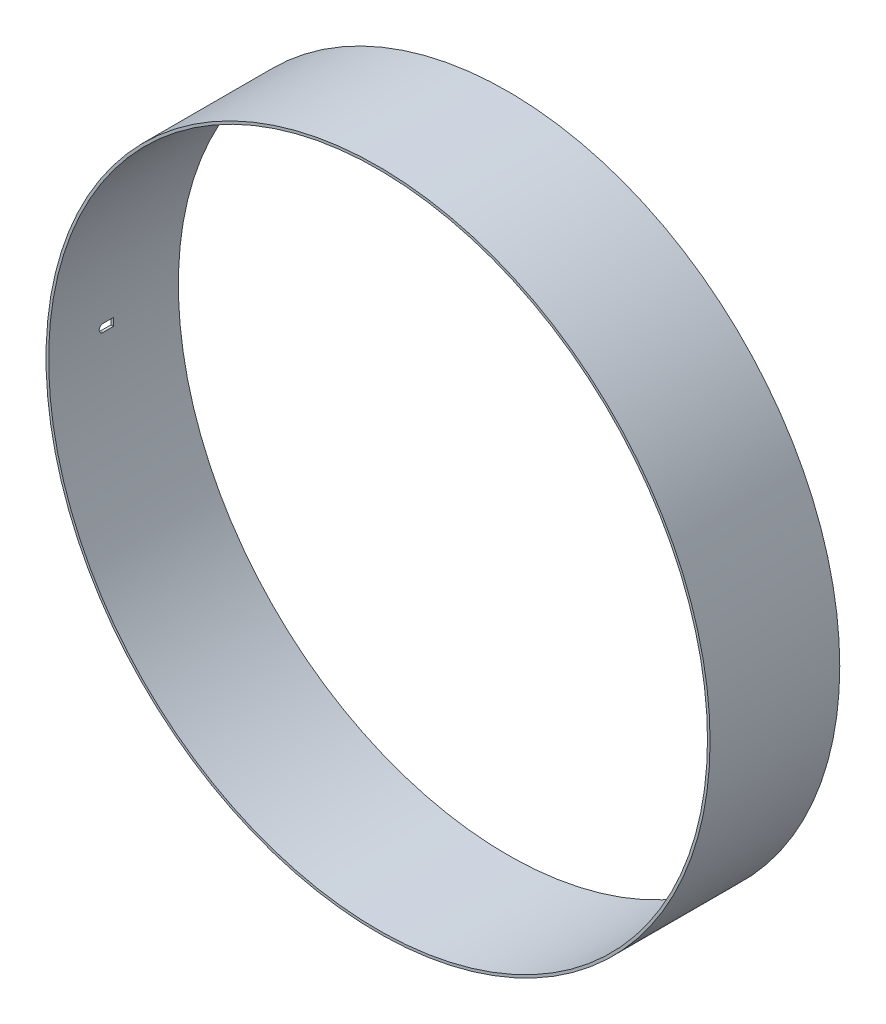
SolidWorks part; units mm, degrees
ref_plane "前视基准面" through (0, 0, 0) normal (0, 0, 1) x (1, 0, 0)
ref_plane "上视基准面" through (0, 0, 0) normal (0, 1, 0) x (1, 0, 0)
ref_plane "右视基准面" through (0, 0, 0) normal (1, 0, 0) x (0, 0, -1)
sketch "草图1" plane through (0, 0, 0) normal (0, 0, 1) x (1, 0, 0)
  circle A0 centre (0, 0) radius 64
  circle A1 centre (0, 0) radius 63.5
  dimension "D1" = 128
  dimension "D2" = 127
extrude "凸台-拉伸1" add sketch "草图1" along normal blind 25
sketch "草图2" plane through (0, 0, 0) normal (1, 0, 0) x (0, 0, -1)
  line L0 (-14.5, -0.75) -> (-12.5, -0.75)
  line L1 (-12.5, -0.75) -> (-12.5, 0.75)
  line L2 (-12.5, 0.75) -> (-14.5, 0.75)
  arc A0 (-14.5, 0.75) -> (-14.5, -0.75) centre (-14.5, 0) ccw
  dimension "D1" = 1.5
  dimension "D2" = 2
  dimension "D3" = 14.5
  dimension "D4" = 0
extrude "切除-拉伸1" cut sketch "草图2" against normal blind 2000
